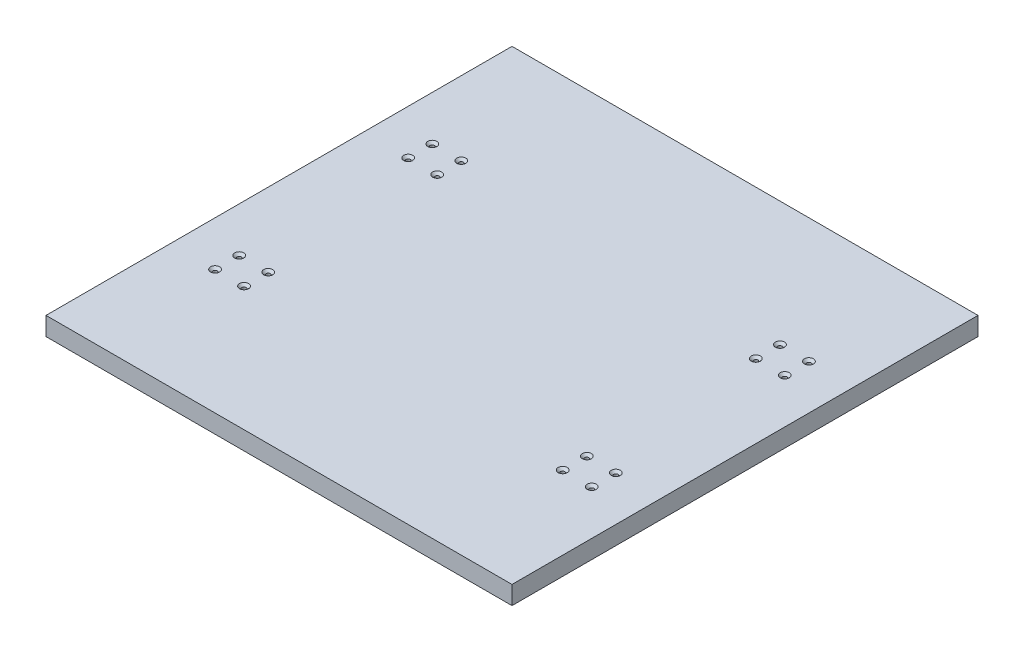
SolidWorks part; units mm, degrees
ref_plane "Front Plane" through (0, 0, 0) normal (0, 0, 1) x (1, 0, 0)
ref_plane "Top Plane" through (0, 0, 0) normal (0, 1, 0) x (1, 0, 0)
ref_plane "Right Plane" through (0, 0, 0) normal (1, 0, 0) x (0, 0, -1)
sketch "Sketch1" plane through (0, 0, 0) normal (0, 1, 0) x (1, 0, 0)
  line L1 (241.3, -241.3) -> (-241.3, -241.3)
  line L2 (241.3, -241.3) -> (241.3, 241.3)
  line L3 (241.3, 241.3) -> (-241.3, 241.3)
  line L4 (-241.3, -241.3) -> (-241.3, 241.3)
  line L5 (241.3, -241.3) -> (-241.3, 241.3) construction
  line L6 (241.3, 241.3) -> (-241.3, -241.3) construction
  point P0 (0, 0)
extrude "Boss-Extrude1" add sketch "Sketch1" along normal blind 19.05
sketch "Sketch2" plane through (0, 19.05, 0) normal (0, 1, 0) x (1, 0, 0)
  line L2 (241.3, 0) -> (-241.3, 0) construction
  line L5 (241.3, -241.3) -> (241.3, 241.3) construction
  line L6 (-241.3, 241.3) -> (-241.3, -241.3) construction
  line L7 (0, -241.3) -> (0, 241.3) construction
  line L10 (-241.3, -241.3) -> (241.3, -241.3) construction
  line L11 (241.3, 241.3) -> (-241.3, 241.3) construction
  point P0 (-195, -87.5)
  point P1 (-165, -87.5)
  point P2 (-165, -112.5)
  point P3 (-195, -112.5)
  point P4 (195, -112.5)
  point P5 (165, -112.5)
  point P10 (165, -87.5)
  point P11 (195, -87.5)
  point P29 (195, 87.5)
  point P30 (195, 112.5)
  point P31 (165, 112.5)
  point P32 (165, 87.5)
  point P33 (-195, 87.5)
  point P34 (-165, 87.5)
  point P35 (-165, 112.5)
  point P36 (-195, 112.5)
  dimension "D1" = 30
  dimension "D2" = 25
  dimension "D5" = 165
  dimension "D6" = 87.5
  dimension "D7" = 482.6
  dimension "D8" = 482.6
hole_wizard "CSK for M4 Flat Head Machine Screw1" positions "Sketch2" profile "Sketch3" countersink size "M4" standard "ANSI Metric" end condition up to next
sketch "Sketch3" plane through (-195, 19.05, 87.5) normal (1, 0, 0) x (0, 0, 1)
  line L0 (0, 0) -> (0, 19.05)
  line L1 (0, 19.05) -> (2.25, 19.05)
  line L2 (2.25, 19.05) -> (2.25, 2.45)
  line L3 (2.25, 2.45) -> (4.7, 0)
  line L5 (4.7, 0) -> (0, 0)
  line L6 (-2.25, 2.45) -> (-4.7, 0) construction
  line L11 (0, -6.35) -> (0, 107.95) construction
  dimension "Thru Hole Dia." = 4.5
  dimension "Thru Hole Depth" = 19.05
  dimension "Near C'Sink Dia." = 9.4
  dimension "Near C'Sink Angle" = 90
